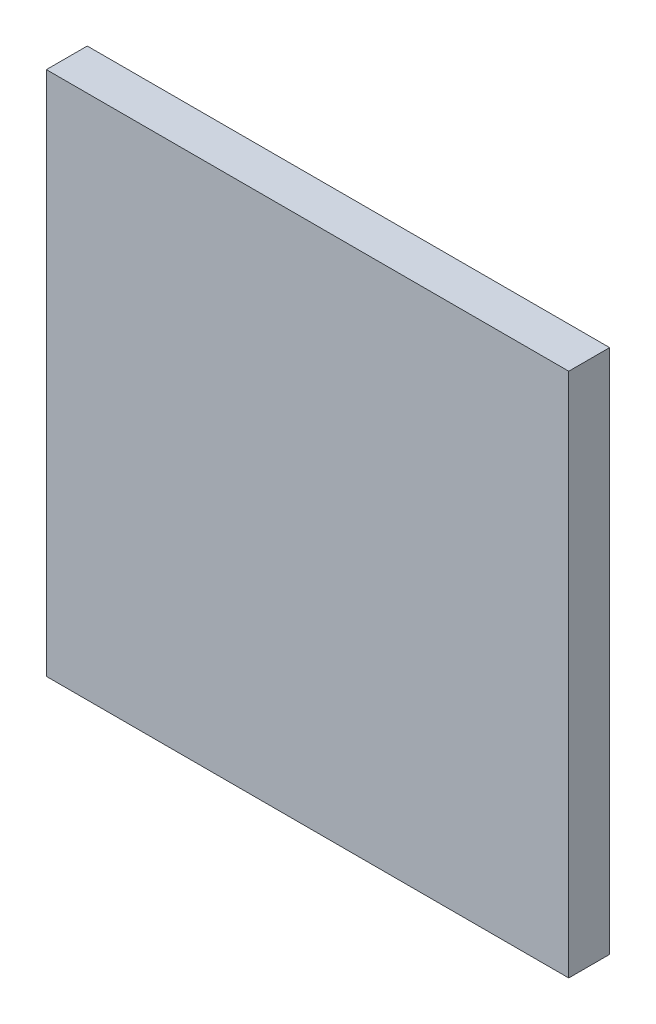
SolidWorks part; units mm, degrees
ref_plane "Front Plane" through (0, 0, 0) normal (0, 0, 1) x (1, 0, 0)
ref_plane "Top Plane" through (0, 0, 0) normal (0, 1, 0) x (1, 0, 0)
ref_plane "Right Plane" through (0, 0, 0) normal (1, 0, 0) x (0, 0, -1)
sketch "Sketch1" plane through (0, 0, 0) normal (0, 0, 1) x (1, 0, 0)
  line L0 (-6.4262, 6.4262) -> (6.35, 6.4262)
  line L1 (6.35, 6.4262) -> (6.35, -6.4262)
  line L2 (6.35, -6.4262) -> (-6.4262, -6.4262)
  line L3 (-6.4262, -6.4262) -> (-6.4262, 6.4262)
extrude "Component_Outline" add sketch "Sketch1" along normal blind 1 separate body
sketch3d "3DSketch1"
  line L0 (0, 0, 0) -> (1, 0, 0)
  line L1 (0, 0, 0) -> (0, 1, 0)
  line L2 (0, 0, 0) -> (0, 0, 1)
  point P0 (0, 0, 0)
